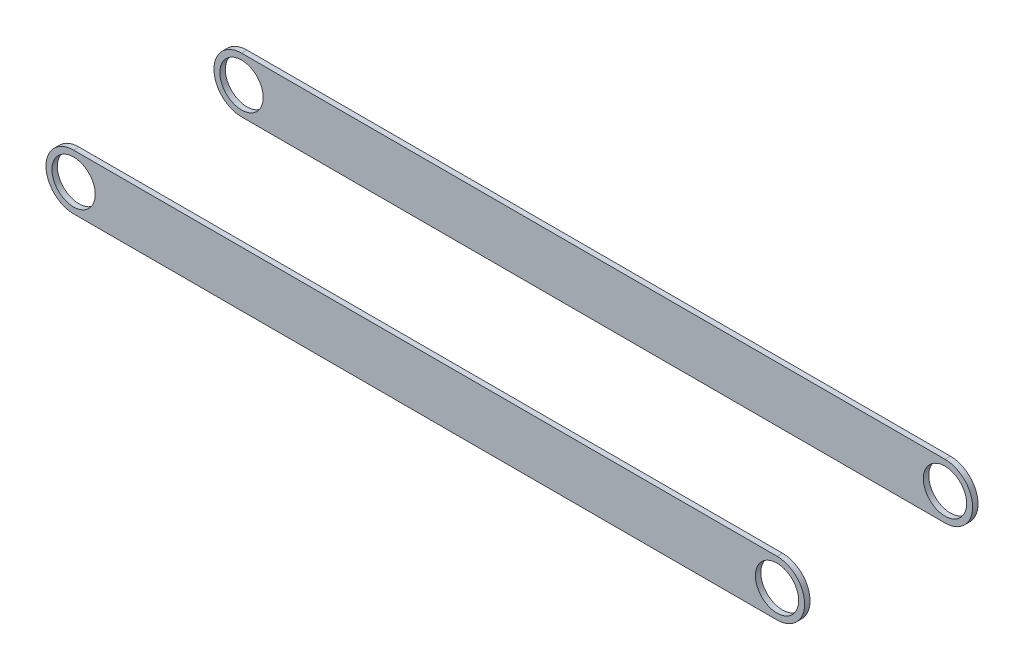
SolidWorks part; units mm, degrees
ref_plane "Front Plane" through (0, 0, 0) normal (0, 0, 1) x (1, 0, 0)
ref_plane "Top Plane" through (0, 0, 0) normal (0, 1, 0) x (1, 0, 0)
ref_plane "Right Plane" through (0, 0, 0) normal (1, 0, 0) x (0, 0, -1)
sketch "Sketch1" plane through (0, 0, 0) normal (0, 0, 1) x (1, 0, 0)
  line L0 (0, 0) -> (-1300, 0) construction
  line L1 (0, -51) -> (-1300, -51)
  line L2 (0, 51) -> (-1300, 51)
  line L3 (-601.0662, 0) -> (-957.0822, 0)
  arc A0 (0, -51) -> (0, 51) centre (0, 0) ccw
  arc A1 (-1300, 51) -> (-1300, -51) centre (-1300, 0) ccw
  circle A2 centre (0, 0) radius 40
  circle A3 centre (-1300, 0) radius 40
  point P3 (-650, 0)
  dimension "D1" = 51
  dimension "D3" = 80
  dimension "D4" = 80
  dimension "D2" = 1300
  dimension "D5" = 0
extrude "Boss-Extrude1" add sketch "Sketch1" along normal blind 10
ref_plane "Plane12" through (0, 0, 315) normal (0, 0, 1) x (1, 0, 0)
mirror "Mirror5" about plane through (0, 0, 315) normal (0, 0, 1) of bodies 101 116
move or copy body "实体-移动/复制1" bodies to move or copy 119 copy no translate (0, 0, -113.8) parameters "D1"=0, "D2"=0, "D3"=113.8
move or copy body "实体-移动/复制2" bodies to move or copy 101 copy no translate (0, 0, 113.8) parameters "D1"=0, "D2"=0, "D3"=113.8
move or copy body "实体-移动/复制4" bodies to move or copy 121 copy no translate (0, 0, 41) parameters "D1"=0, "D2"=0, "D3"=41
move or copy body "实体-移动/复制5" bodies to move or copy 120 copy no translate (0, 0, -41) parameters "D1"=0, "D2"=0, "D3"=41
equation "\"113.8.00mm\"=200"
